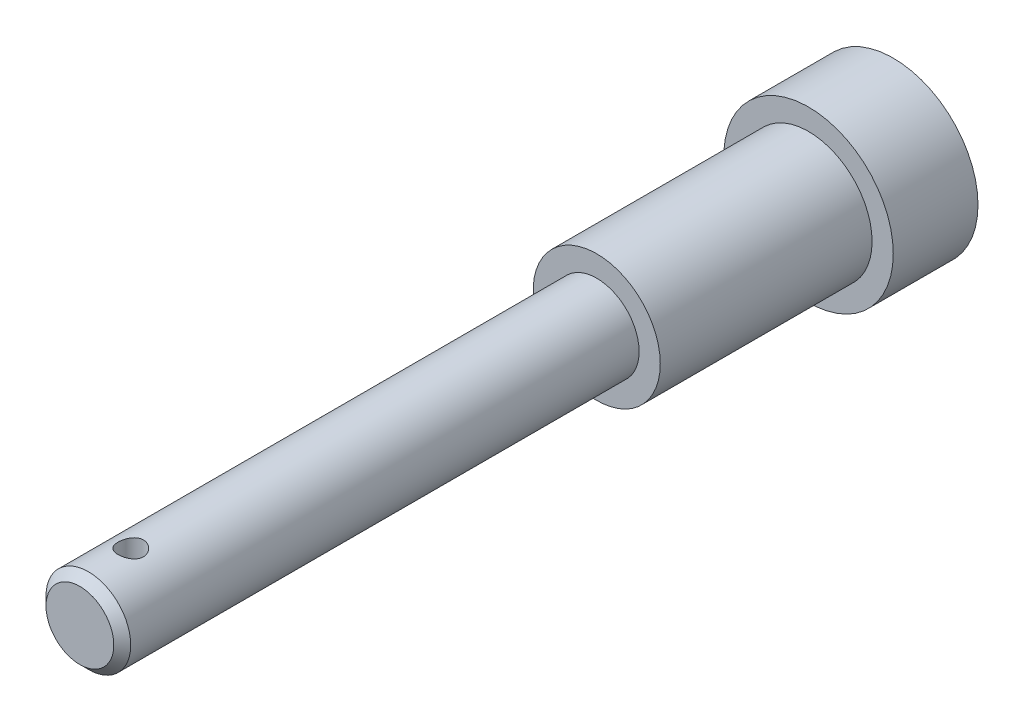
SolidWorks part; units mm, degrees
ref_plane "Front Plane" through (0, 0, 0) normal (0, 0, 1) x (1, 0, 0)
ref_plane "Top Plane" through (0, 0, 0) normal (0, 1, 0) x (1, 0, 0)
ref_plane "Right Plane" through (0, 0, 0) normal (1, 0, 0) x (0, 0, -1)
sketch "Sketch1" plane through (0, 0, 0) normal (0, 0, 1) x (1, 0, 0)
  circle A0 centre (0, 0) radius 20
  dimension "D1" = 40
extrude "Boss-Extrude1" add sketch "Sketch1" along normal blind 20
sketch "Sketch2" plane through (0, 0, 20) normal (0, 0, 1) x (1, 0, 0)
  circle A0 centre (0, 0) radius 15
  dimension "D1" = 30
extrude "Boss-Extrude2" add sketch "Sketch2" along normal blind 50
sketch "Sketch3" plane through (0, 0, 70) normal (0, 0, 1) x (1, 0, 0)
  circle A0 centre (0, 0) radius 10
  dimension "D1" = 20
extrude "Boss-Extrude3" add sketch "Sketch3" along normal blind 120
sketch "Sketch5" plane through (0, 0, 0) normal (1, 0, 0) x (0, 0, -1)
  line L0 (30.3653, 0) -> (-275.4926, 0) construction
  line L1 (-190, 0) -> (-192, 0)
  line L2 (-190, 10) -> (-190, -10) construction
  line L3 (-192, 0) -> (-192, -8)
  line L4 (-192, -8) -> (-190, -10)
  line L5 (-190, -10) -> (-190, 0)
  dimension "D1" = 2
  dimension "D2" = 45
revolve "Revolve1" add sketch "Sketch5" angle 360 about L0
sketch "Sketch6" plane through (0, 0, 0) normal (0, 1, 0) x (1, 0, 0)
  line L0 (10, -190) -> (-10, -190) construction
  line L1 (-10, -70) -> (-10, -190) construction
  circle A0 centre (0, -180) radius 3
  dimension "D1" = 10
  dimension "D2" = 6
  dimension "D3" = 10
extrude "Cut-Extrude1" cut sketch "Sketch6" against normal mid plane 44
